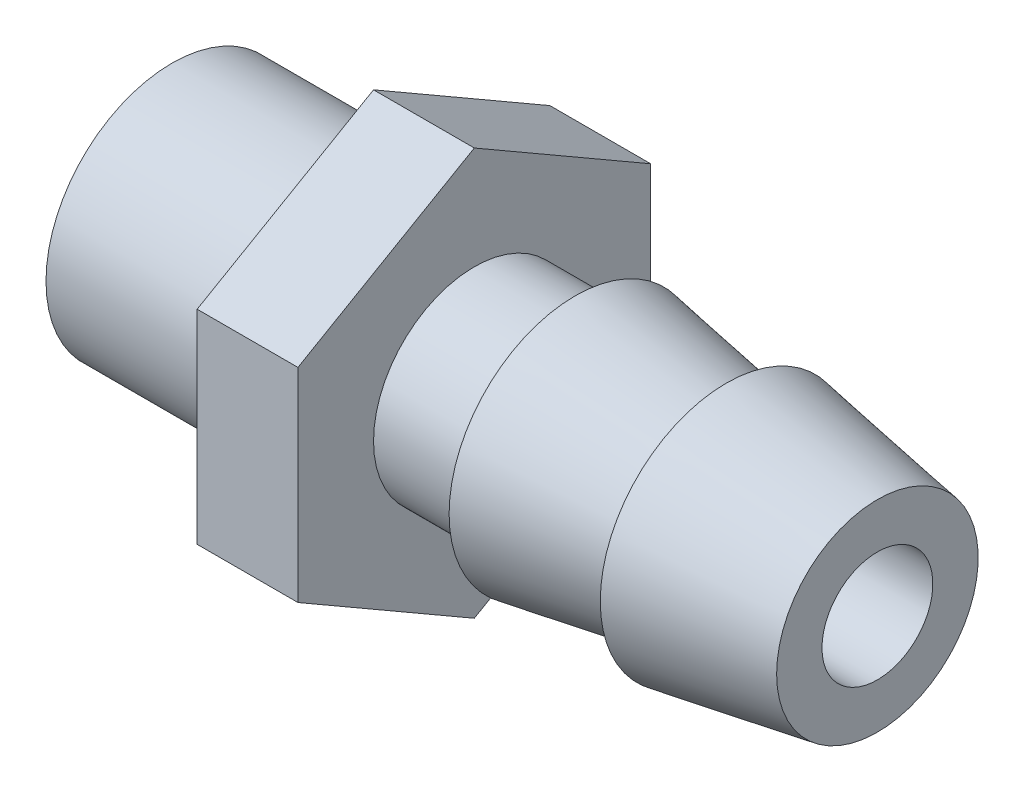
SolidWorks part; units mm, degrees
ref_plane "Front" through (0, 0, 0) normal (0, 0, 1) x (1, 0, 0)
ref_plane "Top" through (0, 0, 0) normal (0, 1, 0) x (1, 0, 0)
ref_plane "Right" through (0, 0, 0) normal (1, 0, 0) x (0, 0, -1)
sketch "Esquisse4" plane through (0, 0, 0) normal (0, 0, 1) x (1, 0, 0)
  line L0 (0, 0) -> (10, 0) construction
  line L3 (10, 1.1) -> (10, 2)
  line L4 (10, 2) -> (7, 2.5)
  line L5 (7, 2.5) -> (7, 2)
  line L6 (7, 2) -> (4, 2.5)
  line L7 (4, 2.5) -> (4, 2)
  line L8 (4, 2) -> (2, 2)
  line L9 (2, 2) -> (2, 5)
  line L10 (2, 5) -> (0, 5)
  line L11 (0, 5) -> (0, 2.5)
  line L12 (-4, 1.1) -> (10, 1.1)
  line L23 (-4, 1.1) -> (-4, 2.5)
  line L24 (-4, 2.5) -> (0, 2.5)
  dimension "D1" = 4
  dimension "D2" = 10
  dimension "D3" = 3
  dimension "D4" = 2
  dimension "D5" = 2.2
  dimension "D6" = 5
  dimension "D7" = 10
  dimension "D8" = 14
  dimension "D9" = 2
  dimension "D10" = 4
  dimension "D11" = 5
revolve "Révolution2" add sketch "Esquisse4" angle 360 about L0
sketch "Esquisse5" plane through (2, 0, 0) normal (1, 0, 0) x (0, 0, -1)
  line L1 (0, -4.0415) -> (3.5, -2.0207)
  line L2 (3.5, -2.0207) -> (3.5, 2.0207)
  line L3 (3.5, 2.0207) -> (0, 4.0415)
  line L4 (0, 4.0415) -> (-3.5, 2.0207)
  line L5 (-3.5, 2.0207) -> (-3.5, -2.0207)
  line L6 (-3.5, -2.0207) -> (0, -4.0415)
  circle A0 centre (0, 0) radius 3.5 construction
  dimension "D1" = 7
  dimension "D2" = 8.0829
extrude "Enlèv. mat.-Extru.1" cut sketch "Esquisse5" against normal up to surface (2 mm away) flip side to cut up to face at (0, 0, 2.5)
